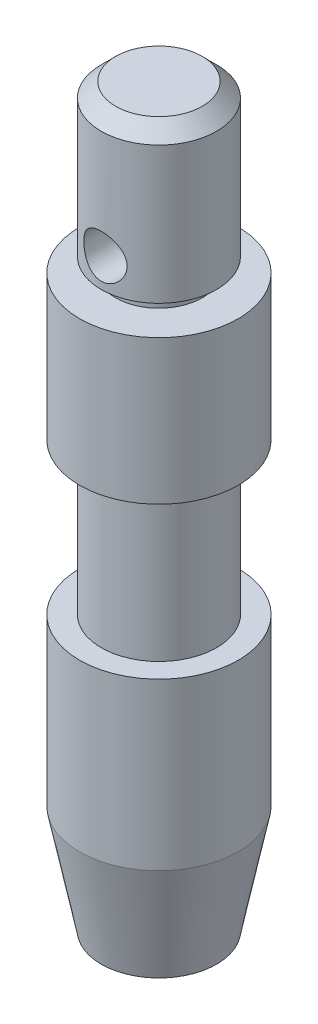
SolidWorks part; units mm, degrees
material "Acier allié (SS)"
ref_plane "Plan de face" through (0, 0, 0) normal (0, 0, 1) x (1, 0, 0)
ref_plane "Plan de dessus" through (0, 0, 0) normal (0, 1, 0) x (1, 0, 0)
ref_plane "Plan de droite" through (0, 0, 0) normal (1, 0, 0) x (0, 0, -1)
sketch "Esquisse2" plane through (0, 0, 0) normal (0, 1, 0) x (1, 0, 0)
  circle A0 centre (0, 0) radius 5.5
  dimension "D1" = 11
extrude "Boss.-Extru.2" add sketch "Esquisse2" along normal blind 19 contours A0
chamfer "Chanfrein1" distance 1.5 distance2 7.5 1 edges at (0, 0, 5.5)
sketch "Esquisse8" plane through (0, 19, 0) normal (0, 1, 0) x (1, 0, 0)
  circle A0 centre (0, 0) radius 4
  dimension "D1" = 8
extrude "Boss.-Extru.3" add sketch "Esquisse8" along normal blind 10.5
sketch "Esquisse9" plane through (0, 29.5, 0) normal (0, 1, 0) x (1, 0, 0)
  circle A0 centre (0, 0) radius 5.5
  dimension "D1" = 11
extrude "Boss.-Extru.4" add sketch "Esquisse9" along normal blind 10
sketch "Esquisse10" plane through (0, 39.5, 0) normal (0, 1, 0) x (1, 0, 0)
  circle A0 centre (0, 0) radius 3
  dimension "D1" = 6
extrude "Boss.-Extru.5" add sketch "Esquisse10" along normal blind 1
sketch "Esquisse12" plane through (0, 40.5, 0) normal (0, 1, 0) x (1, 0, 0)
  circle A0 centre (0, 0) radius 4
  dimension "D1" = 8
extrude "Boss.-Extru.6" add sketch "Esquisse12" along normal blind 10.5
chamfer "Chanfrein2" distance 1 distance2 1 1 edges at (0, 51, 4)
sketch "Esquisse15" plane through (0, 0, 0) normal (0, 0, 1) x (1, 0, 0)
  line L0 (0, 40.5) -> (0, 42.5)
  line L1 (-3, 40.5) -> (3, 40.5) construction
  circle A0 centre (0, 42.5) radius 1.5
  dimension "D2" = 3
  dimension "D1" = 2
extrude "Enlèv. mat.-Extru.1" cut sketch "Esquisse15" against normal through all both and the other way through all contours A0
